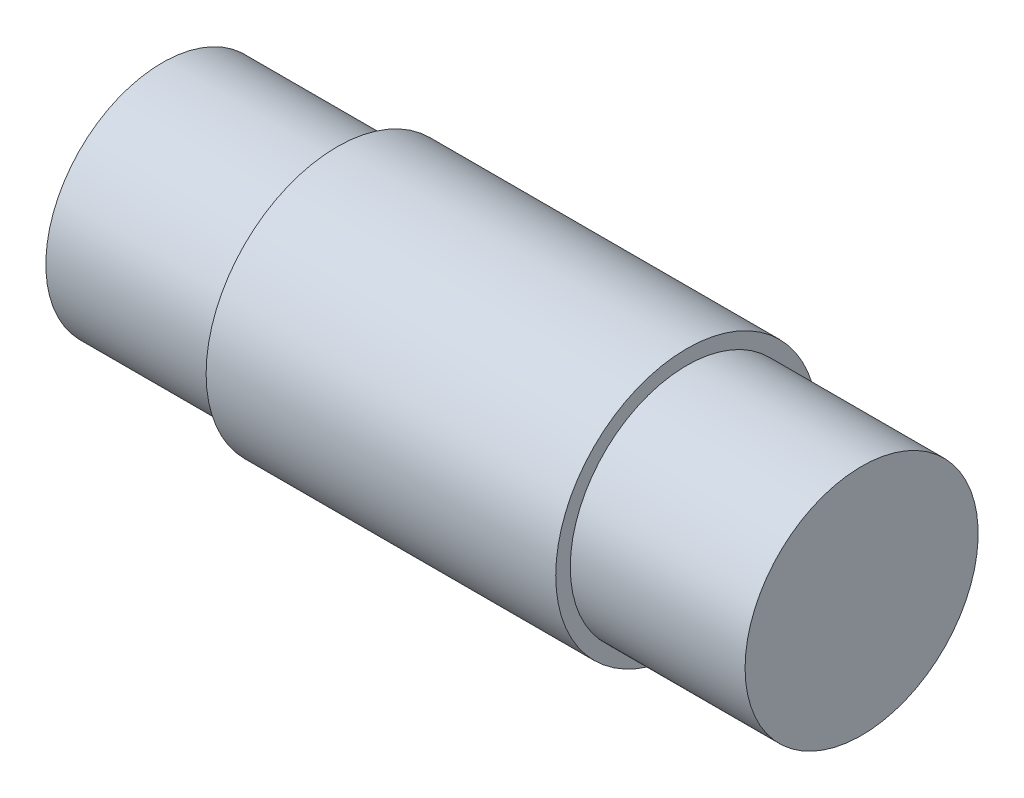
SolidWorks part; units mm, degrees
ref_plane "Front Plane" through (0, 0, 0) normal (0, 0, 1) x (1, 0, 0)
ref_plane "Top Plane" through (0, 0, 0) normal (0, 1, 0) x (1, 0, 0)
ref_plane "Right Plane" through (0, 0, 0) normal (1, 0, 0) x (0, 0, -1)
sketch "Sketch2" plane through (0, 0, 0) normal (1, 0, 0) x (0, 0, -1)
  circle A0 centre (0, 0) radius 3.175
  dimension "D1" = 6.35
extrude "Boss-Extrude1" add sketch "Sketch2" along normal mid plane 4.7625
sketch "Sketch3" plane through (-2.3813, 0, 0) normal (-1, 0, 0) x (0, 0, 1)
  circle A0 centre (0, 0) radius 3.5712
  dimension "D1" = 7.1425
extrude "Boss-Extrude2" add sketch "Sketch3" along normal blind 9.525
sketch "Sketch5" plane through (-11.9062, 0, 0) normal (-1, 0, 0) x (0, 0, 1)
  circle A0 centre (0, 0) radius 3.175
  dimension "D1" = 6.35
extrude "Boss-Extrude3" add sketch "Sketch5" along normal blind 4.7625
